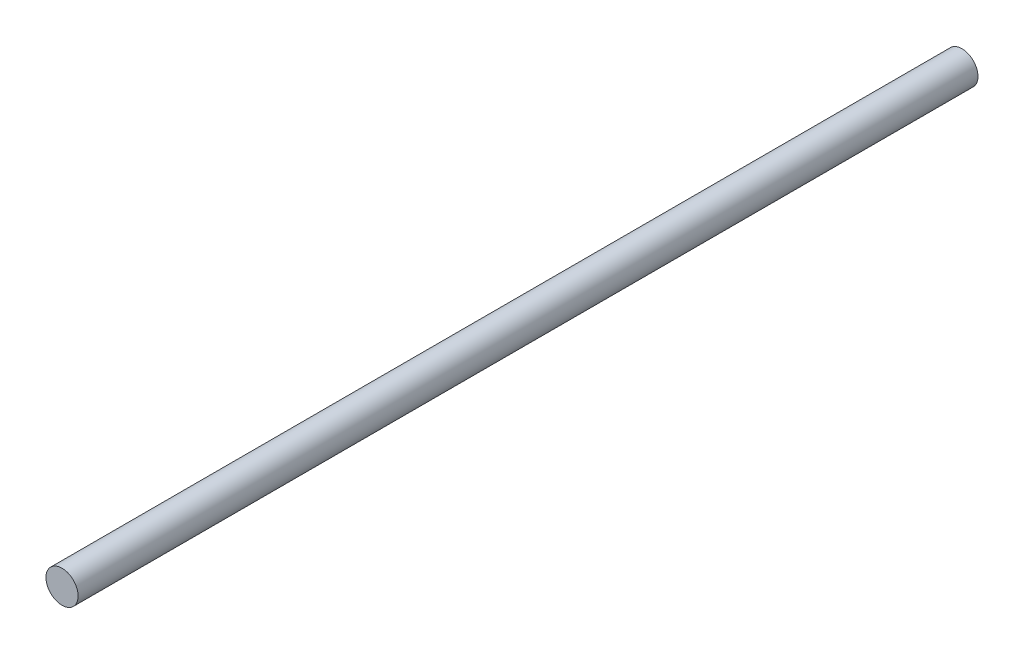
SolidWorks part; units mm, degrees
ref_plane "前视基准面" through (0, 0, 0) normal (0, 0, 1) x (1, 0, 0)
ref_plane "上视基准面" through (0, 0, 0) normal (0, 1, 0) x (1, 0, 0)
ref_plane "右视基准面" through (0, 0, 0) normal (1, 0, 0) x (0, 0, -1)
sketch "草图1" plane through (0, 0, 0) normal (0, 0, 1) x (1, 0, 0)
  circle A0 centre (0, 0) radius 12.5
extrude "凸台-拉伸1" add sketch "草图1" along normal blind 700
